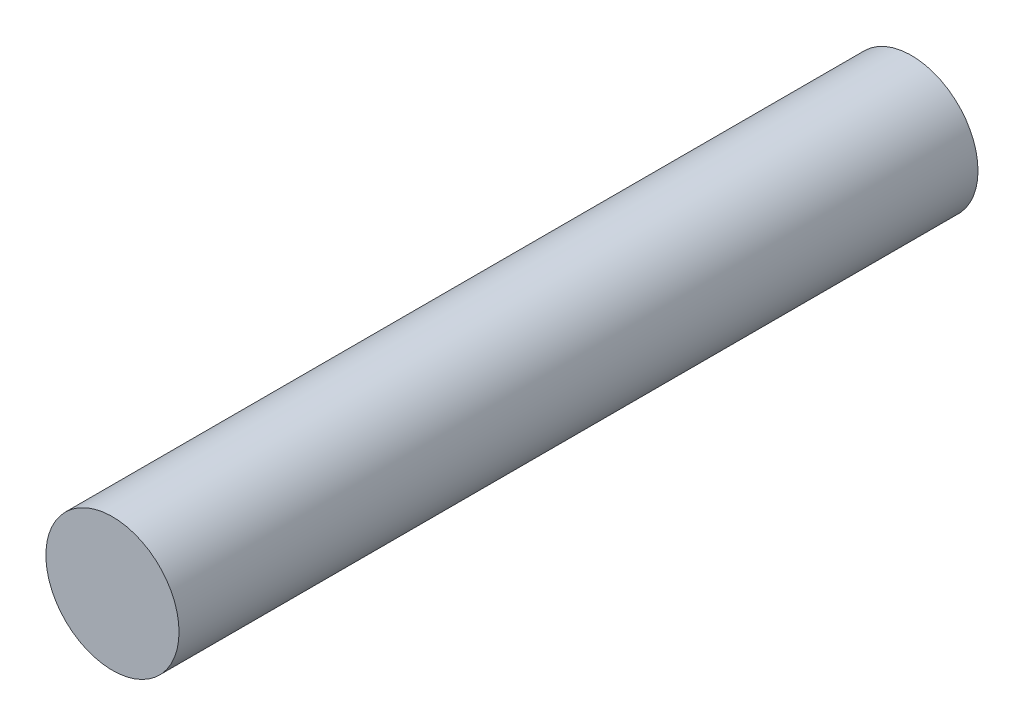
SolidWorks part; units mm, degrees
ref_plane "Front" through (0, 0, 0) normal (0, 0, 1) x (1, 0, 0)
ref_plane "Top" through (0, 0, 0) normal (0, 1, 0) x (1, 0, 0)
ref_plane "Right" through (0, 0, 0) normal (1, 0, 0) x (0, 0, -1)
sketch "Sketch1" plane through (0, 0, 0) normal (0, 0, 1) x (1, 0, 0)
  circle A0 centre (0, 0) radius 25.4 construction
  circle A1 centre (0, 0) radius 25.4
extrude "Extrude1" add sketch "Sketch1" against normal blind 304.8
